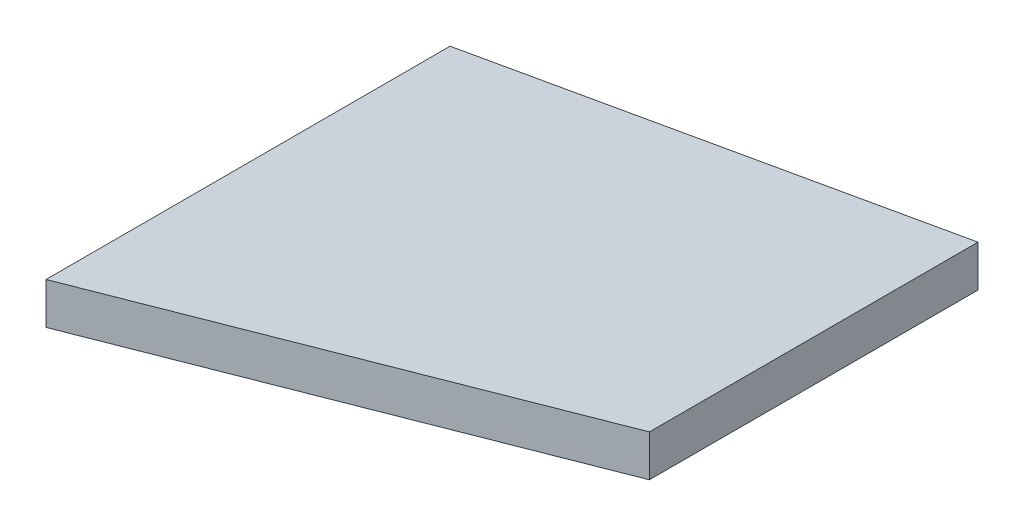
SolidWorks part; units mm, degrees
ref_plane "Ön Düzlem" through (0, 0, 0) normal (0, 0, 1) x (1, 0, 0)
ref_plane "Üst Düzlem" through (0, 0, 0) normal (0, 1, 0) x (1, 0, 0)
ref_plane "Sağ Düzlem" through (0, 0, 0) normal (1, 0, 0) x (0, 0, -1)
sketch "Sketch2" plane through (0, 0, 0) normal (0, 0, 1) x (1, 0, 0)
  line L0 (140, 42.9353) -> (140, 32.6667)
  line L1 (140, 32.6667) -> (0, 0)
  line L2 (0, 0) -> (0, 10.2686)
  line L3 (0, 10.2686) -> (140, 42.9353)
extrude "Boss-Extrude1" add sketch "Sketch2" along normal blind 100
sketch "Sketch4" plane through (0, 0, 0) normal (0, 1, 0) x (1, 0, 0)
  line L0 (0, 0) -> (140, 0)
  line L1 (140, 0) -> (140, -9.3333)
  line L2 (140, -9.3333) -> (0, 0)
  line L3 (0, -50) -> (140, -50) construction
  line L4 (0, -100) -> (0, 0) construction
  line L5 (140, -100) -> (140, 0) construction
  line L6 (140, -90.6667) -> (0, -100)
  line L7 (140, -100) -> (140, -90.6667)
  line L8 (0, -100) -> (140, -100)
extrude "Cut-Extrude1" cut sketch "Sketch4" along normal blind 65
